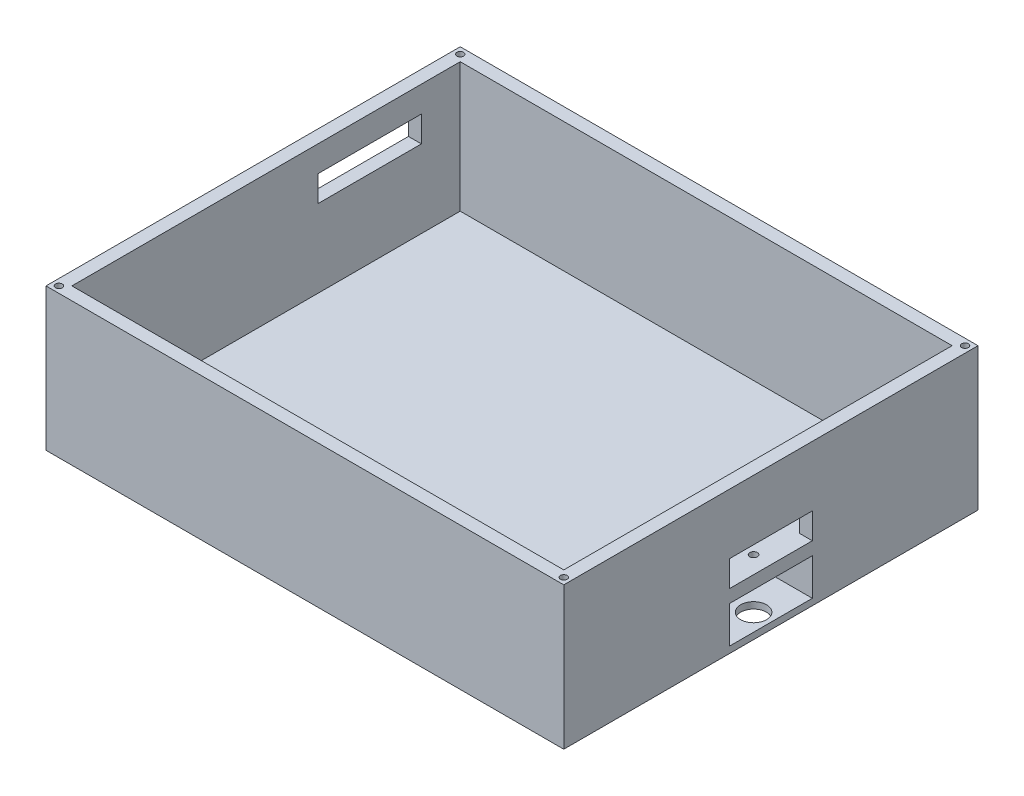
SolidWorks part; units mm, degrees
ref_plane "Front Plane" through (0, 0, 0) normal (0, 0, 1) x (1, 0, 0)
ref_plane "Top Plane" through (0, 0, 0) normal (0, 1, 0) x (1, 0, 0)
ref_plane "Right Plane" through (0, 0, 0) normal (1, 0, 0) x (0, 0, -1)
sketch "Sketch1" plane through (0, 0, 0) normal (0, 1, 0) x (1, 0, 0)
  line L1 (-127, -101.6) -> (127, -101.6)
  line L2 (-127, -101.6) -> (-127, 101.6)
  line L3 (-127, 101.6) -> (127, 101.6)
  line L4 (127, -101.6) -> (127, 101.6)
  line L5 (-127, -101.6) -> (127, 101.6) construction
  line L6 (-127, 101.6) -> (127, -101.6) construction
  point P0 (0, 0)
  dimension "D1" = 254
  dimension "D2" = 203.2
extrude "Boss-Extrude1" add sketch "Sketch1" along normal blind 6.35
sketch "Sketch2" plane through (0, 6.35, 0) normal (0, 1, 0) x (1, 0, 0)
  line L0 (127, -101.6) -> (127, 101.6) construction
  line L1 (-127, 101.6) -> (127, 101.6)
  line L2 (-127, 101.6) -> (-127, 95.25)
  line L3 (-127, 95.25) -> (127, 95.25)
  line L4 (127, 101.6) -> (127, 95.25)
  line L5 (-127, 101.6) -> (-127, -101.6) construction
  line L6 (127, -101.6) -> (-127, -101.6)
  line L7 (127, -101.6) -> (127, -95.25)
  line L8 (127, -95.25) -> (-127, -95.25)
  line L9 (-127, -101.6) -> (-127, -95.25)
  line L11 (-127, -95.25) -> (-120.65, -95.25)
  line L12 (-127, -95.25) -> (-127, 95.25)
  line L13 (-127, 95.25) -> (-120.65, 95.25)
  line L14 (-120.65, -95.25) -> (-120.65, 95.25)
  line L15 (127, 95.25) -> (120.65, 95.25)
  line L16 (127, 95.25) -> (127, -95.25)
  line L17 (127, -95.25) -> (120.65, -95.25)
  line L18 (120.65, 95.25) -> (120.65, -95.25)
  line M13 (127, -101.6) -> (127, 101.6)
  line M14 (127, 101.6) -> (-127, 101.6)
  line M15 (-127, 101.6) -> (-127, -101.6)
  line M16 (-127, -101.6) -> (127, -101.6)
  dimension "D1" = 6.35
extrude "Boss-Extrude2" add sketch "Sketch2" along normal blind 63.5 contours L8 L14 L3 M15 | L3 M15 M13 M14 | L3 L18 L8 M13 | L8 M13 M15 M16
sketch "Sketch3" plane through (0, 69.85, 0) normal (0, 1, 0) x (1, 0, 0)
  line L0 (120.65, 95.25) -> (120.65, -95.25) construction
  line L1 (120.65, 20.32) -> (127, 20.32)
  line L2 (120.65, 20.32) -> (120.65, -20.32)
  line L3 (120.65, -20.32) -> (127, -20.32)
  line L4 (127, 20.32) -> (127, -20.32)
  line L5 (127, -101.6) -> (127, 101.6) construction
  point P8 (120.65, 0)
  dimension "D1" = 40.64
extrude "Cut-Extrude1" cut sketch "Sketch3" against normal up to surface (63.5 mm away) up to face at (0, 6.35, 0)
sketch "Sketch4" plane through (0, 6.35, 0) normal (0, 1, 0) x (1, 0, 0)
  line L0 (120.65, -20.32) -> (127, -20.32) construction
  line L1 (127, 20.32) -> (76.2, 20.32)
  line L2 (127, 20.32) -> (127, -20.32)
  line L3 (127, -20.32) -> (76.2, -20.32)
  line L4 (76.2, 20.32) -> (76.2, -20.32)
  dimension "D1" = 50.8
extrude "Cut-Extrude2" cut sketch "Sketch4" against normal blind 3.175
sketch "Sketch5" plane through (0, 6.35, 0) normal (0, 1, 0) x (1, 0, 0)
  line L1 (120.65, 20.32) -> (88.9, 20.32)
  line L2 (120.65, 20.32) -> (120.65, 26.67)
  line L3 (120.65, 26.67) -> (88.9, 26.67)
  line L4 (88.9, 20.32) -> (88.9, 26.67)
  dimension "D1" = 31.75
  dimension "D2" = 6.35
extrude "Boss-Extrude3" add sketch "Sketch5" along normal up to surface (14.913 mm away)
sketch "Sketch6" plane through (0, 21.263, 0) normal (0, 1, 0) x (1, 0, 0)
  line L1 (88.9, 26.67) -> (127, 26.67)
  line L2 (88.9, 26.67) -> (88.9, 0)
  line L3 (88.9, 0) -> (127, 0)
  line L4 (127, 26.67) -> (127, 0)
  line L5 (127, 20.32) -> (127, 101.6) construction
extrude "Boss-Extrude4" add sketch "Sketch6" along normal blind 6.35
mirror "Mirror1" about plane through (0, 0, 0) normal (0, 0, 1) of "Boss-Extrude4", "Boss-Extrude3"
sketch "Sketch7" plane through (0, 27.613, 0) normal (0, 1, 0) x (1, 0, 0)
  circle A0 centre (99.4, 0) radius 1.85 construction
  circle A1 centre (118.5, 0) radius 1.85 construction
  circle A2 centre (99.4, 0) radius 1.85
  circle A3 centre (118.5, 0) radius 1.85
extrude "Cut-Extrude3" cut sketch "Sketch7" against normal up to next
sketch "Sketch8" plane through (0, 69.85, 0) normal (0, 1, 0) x (1, 0, 0)
  line L0 (-127, 101.6) -> (-127, -101.6) construction
  line L1 (-127, 76.2) -> (-120.65, 76.2)
  line L2 (-127, 76.2) -> (-127, 25.4)
  line L3 (-127, 25.4) -> (-120.65, 25.4)
  line L4 (-120.65, 76.2) -> (-120.65, 25.4)
  line L5 (-120.65, -95.25) -> (-120.65, 95.25) construction
  line L6 (127, 101.6) -> (-127, 101.6) construction
  dimension "D1" = 50.8
  dimension "D2" = 25.4
extrude "Cut-Extrude4" cut sketch "Sketch8" against normal blind 25.4
sketch "Sketch9" plane through (0, 0, 0) normal (0, -1, 0) x (1, 0, 0)
  circle A0 centre (99.4, 0) radius 1.85 construction
  circle A1 centre (118.5, 0) radius 1.85 construction
  circle A2 centre (99.4, 0) radius 1.85 construction
  circle A3 centre (118.5, 0) radius 1.85 construction
  circle A4 centre (99.4, 0) radius 6.35
  circle A5 centre (118.5, 0) radius 6.35
  dimension "D1" = 12.7
extrude "Cut-Extrude5" cut sketch "Sketch9" against normal up to next
sketch "Sketch10" plane through (127, 0, 0) normal (1, 0, 0) x (0, 0, -1)
  line L0 (20.32, 27.613) -> (20.32, 69.85) construction
  line L1 (-20.32, 69.85) -> (20.32, 69.85)
  line L2 (-20.32, 69.85) -> (-20.32, 40.313)
  line L3 (-20.32, 40.313) -> (20.32, 40.313)
  line L4 (20.32, 69.85) -> (20.32, 40.313)
  line L5 (-20.32, 27.613) -> (20.32, 27.613) construction
  dimension "D1" = 12.7
extrude "Boss-Extrude5" add sketch "Sketch10" against normal up to surface (6.35 mm away) up to face at (120.65, 34.6043, -47.4133)
sketch "Sketch11" plane through (-127, 0, 0) normal (-1, 0, 0) x (0, 0, 1)
  line L0 (-25.4, 44.45) -> (-25.4, 69.85) construction
  line L1 (-76.2, 69.85) -> (-25.4, 69.85)
  line L2 (-76.2, 69.85) -> (-76.2, 57.15)
  line L3 (-76.2, 57.15) -> (-25.4, 57.15)
  line L4 (-25.4, 69.85) -> (-25.4, 57.15)
  line L6 (-76.2, 44.45) -> (-25.4, 44.45) construction
  dimension "D1" = 12.7
extrude "Boss-Extrude6" add sketch "Sketch11" against normal up to surface (6.35 mm away) up to face at (-120.65, 47.625, -25.4)
sketch "Sketch12" plane through (0, 69.85, 0) normal (0, 1, 0) x (1, 0, 0)
  line L0 (-127, 101.6) -> (-120.65, 95.25) construction
  circle A0 centre (-123.825, 98.425) radius 1.65
  point P6 (0, 0)
  point P7 (-123.825, 98.425)
  dimension "D1" = 3.3
extrude "Cut-Extrude6" cut sketch "Sketch12" against normal blind 12
mirror "Mirror2" about plane through (0, 0, 0) normal (0, 0, 1) of "Cut-Extrude6" second plane through (0, 0, 0) second plane normal (1, 0, 0)
